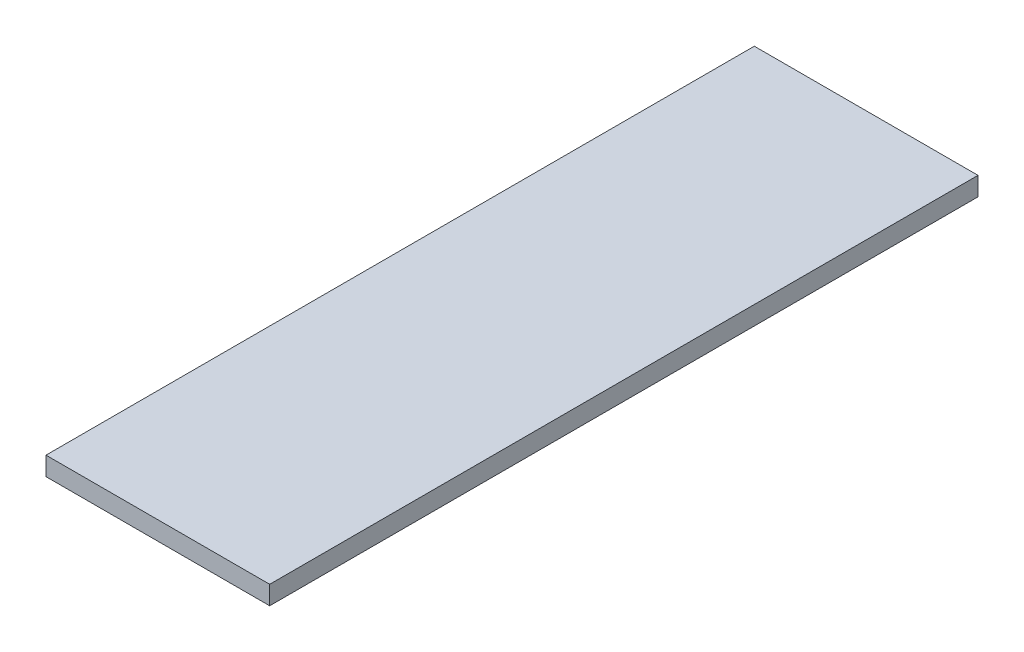
SolidWorks part; units mm, degrees
ref_plane "前视基准面" through (0, 0, 0) normal (0, 0, 1) x (1, 0, 0)
ref_plane "上视基准面" through (0, 0, 0) normal (0, 1, 0) x (1, 0, 0)
ref_plane "右视基准面" through (0, 0, 0) normal (1, 0, 0) x (0, 0, -1)
other "Configuration Table"
sketch "草图1" plane through (0, 0, 0) normal (0, 1, 0) x (1, 0, 0)
  line L1 (-9, -28.5) -> (9, -28.5)
  line L2 (-9, -28.5) -> (-9, 28.5)
  line L3 (-9, 28.5) -> (9, 28.5)
  line L4 (9, -28.5) -> (9, 28.5)
  line L5 (-9, -28.5) -> (9, 28.5) construction
  line L6 (-9, 28.5) -> (9, -28.5) construction
  point P0 (0, 0)
  dimension "D1" = 57
  dimension "D2" = 18
extrude "凸台-拉伸1" add sketch "草图1" along normal blind 1.5
